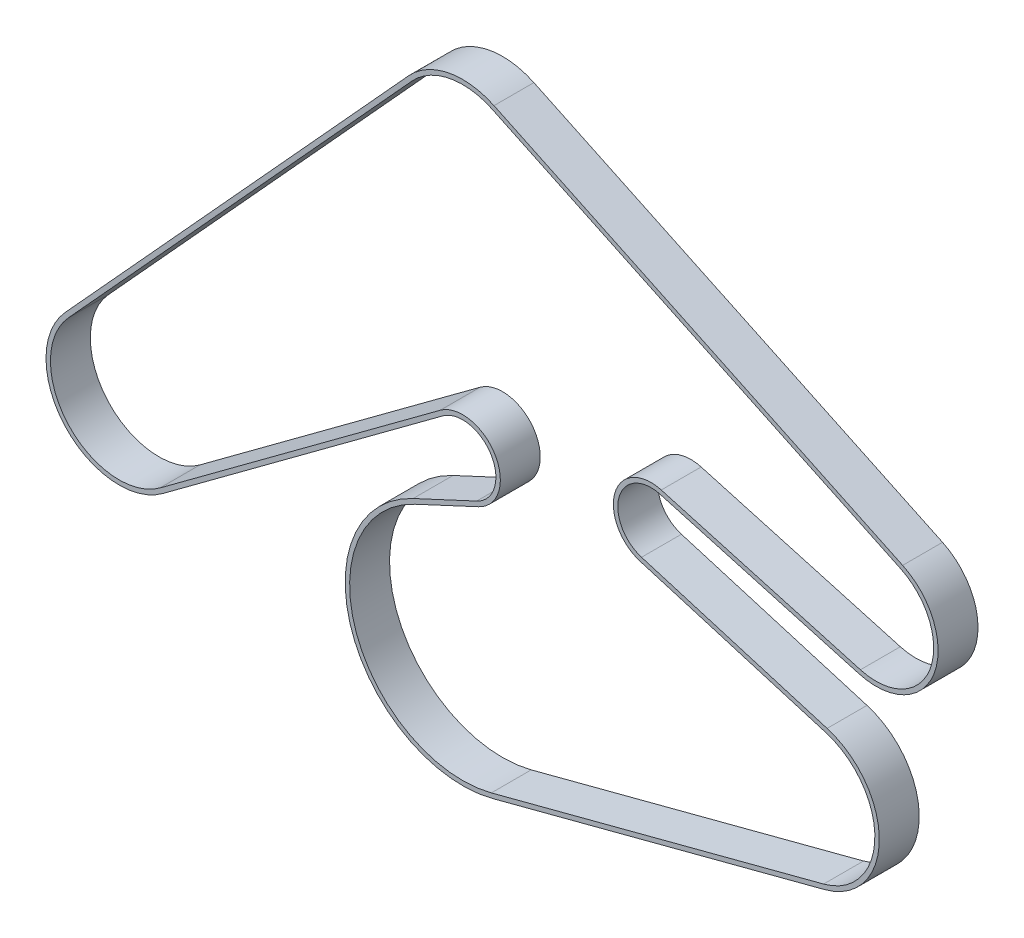
SolidWorks part; units mm, degrees
ref_plane "Front Plane" through (0, 0, 0) normal (0, 0, 1) x (1, 0, 0)
ref_plane "Top Plane" through (0, 0, 0) normal (0, 1, 0) x (1, 0, 0)
ref_plane "Right Plane" through (0, 0, 0) normal (1, 0, 0) x (0, 0, -1)
sketch "Sketch1" plane through (0, 0, 0) normal (0, 0, 1) x (1, 0, 0)
  line L0 (-24.3855, 212.2339) -> (-179.3855, 42.2339)
  line L1 (89.066, 105.4384) -> (178.941, 80.129)
  line L2 (13.4534, -51.2641) -> (163.3767, -11.9191)
  line L3 (164.4432, 51.62) -> (80.7076, 76.6273)
  line L4 (14.1394, 219.8174) -> (198.5278, 132.3803)
  line L5 (-135.3684, -6.5255) -> (-8.9235, 87.057)
  line L6 (6.3277, 61.4) -> (-22.3579, 48.0533)
  circle A0 centre (0, 0) radius 53 construction
  circle A1 centre (-155, 20) radius 33 construction
  circle A2 centre (0, 75) radius 15 construction
  circle A3 centre (85, 91) radius 15 construction
  circle A4 centre (0, 190) radius 33 construction
  circle A5 centre (186.5307, 107.0807) radius 28 construction
  circle A6 centre (155, 20) radius 33 construction
  arc A7 (-24.3855, 212.2339) -> (14.1394, 219.8174) centre (0, 190) cw
  arc A8 (-179.3855, 42.2339) -> (-135.3684, -6.5255) centre (-155, 20) ccw
  arc A9 (-22.3579, 48.0533) -> (13.4534, -51.2641) centre (0, 0) ccw
  arc A10 (164.4432, 51.62) -> (163.3767, -11.9191) centre (155, 20) cw
  arc A11 (178.941, 80.129) -> (198.5278, 132.3803) centre (186.5307, 107.0807) ccw
  arc A12 (89.066, 105.4384) -> (80.7076, 76.6273) centre (85, 91) ccw
  arc A13 (-8.9235, 87.057) -> (6.3277, 61.4) centre (0, 75) cw
  point P0 (0, 190)
  point P1 (0, 75)
  point P2 (85, 91)
  point P3 (0, 0)
  point P4 (155, 20)
  point P5 (186.5307, 107.0807)
  point P6 (-155, 20)
  point P43 (186.5307, 107.0807)
  dimension "D1" = 56
  dimension "D2" = 66
  dimension "D3" = 106
  dimension "D4" = 66
  dimension "D5" = 30
  dimension "D6" = 30
  dimension "D7" = 66
extrude "Extrude-Thin1" add sketch "Sketch1" along normal blind 18 thin thin type one direction reverse wall 2
